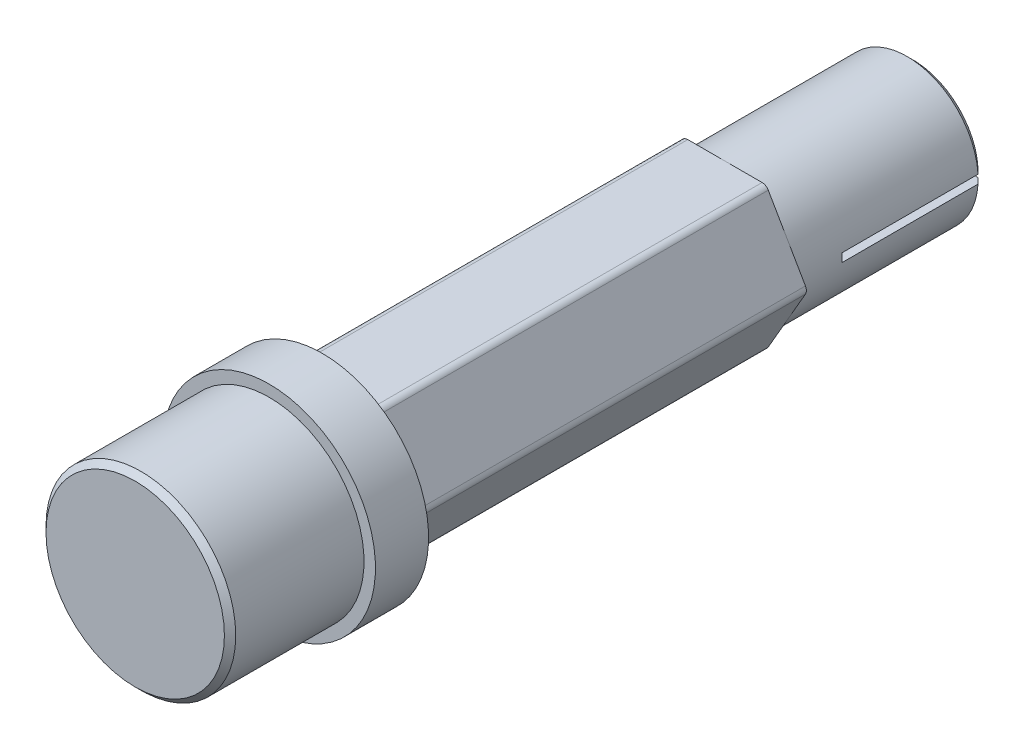
SolidWorks part; units mm, degrees
material "6061-T6 (SS)"
ref_plane "Front Plane" through (0, 0, 0) normal (0, 0, 1) x (1, 0, 0)
ref_plane "Top Plane" through (0, 0, 0) normal (0, 1, 0) x (1, 0, 0)
ref_plane "Right Plane" through (0, 0, 0) normal (1, 0, 0) x (0, 0, -1)
sketch "Sketch1" plane through (0, 0, 0) normal (1, 0, 0) x (0, 0, -1)
  line L0 (0, 0) -> (-33812.0291, 0) construction
  line L1 (0, 0) -> (0, 8.5)
  line L3 (12, 8.5) -> (12, 9.525)
  line L4 (12, 9.525) -> (16.7625, 9.525)
  line L5 (16.7625, 9.525) -> (16.7625, 7.62)
  line L6 (16.7625, 7.62) -> (40.0861, 7.62)
  line L8 (40.0861, 7.62) -> (52.8368, 7.62)
  line L9 (52.8368, 7.62) -> (52.8368, 6.35)
  line L10 (52.8368, 6.35) -> (69.677, 6.35)
  line L11 (69.677, 6.35) -> (69.677, 3.175)
  line L12 (52.5293, 0) -> (0, 0)
  line L16 (0, 8.5) -> (12, 8.5)
  line L17 (69.677, 3.175) -> (54.437, 3.175)
  line L18 (54.437, 3.175) -> (52.5293, 0)
  dimension "D2" = 17
  dimension "D3" = 59
  dimension "D4" = 6.35
  dimension "D5" = 12
  dimension "D6" = 4.7625
  dimension "D7" = 19.05
  dimension "D8" = 15.24
  dimension "D9" = 23.3235
  dimension "D10" = 12.7508
  dimension "D11" = 12.7
  dimension "D12" = 16.8402
  dimension "D13" = 15.24
revolve "Revolve1" add sketch "Sketch1" angle 360 about L0
sketch "Sketch2" plane through (0, 0, -16.7625) normal (0, 0, -1) x (-1, 0, 0)
  line L1 (3.697, 6.4033) -> (-3.697, 6.4033)
  line L2 (-3.697, 6.4033) -> (-7.3939, 0)
  line L3 (-7.3939, 0) -> (-3.697, -6.4033)
  line L4 (-3.697, -6.4033) -> (3.697, -6.4033)
  line L5 (3.697, -6.4033) -> (7.3939, 0)
  line L6 (7.3939, 0) -> (3.697, 6.4033)
  circle A0 centre (0, 0) radius 6.4033 construction
  dimension "D1" = 12.8067
extrude "Cut-Extrude1" cut sketch "Sketch2" along normal up to surface (36.0744 mm away) flip side to cut up to face at (-7.62, 0, -52.8368)
fillet "Fillet1" radius 0.635 6 edges at (3.697, 6.4033, -34.7997) (-3.697, 6.4033, -34.7997) (-7.3939, 0, -34.7997) (-3.697, -6.4033, -34.7997) (3.697, -6.4033, -34.7997) (7.3939, 0, -34.7997)
sketch "Sketch3" plane through (0, 0, -69.677) normal (0, 0, -1) x (-1, 0, 0)
  line L0 (8.9987, 0) -> (0, 0) construction
  line L1 (-8.9987, 0.381) -> (-3.1521, 0.381)
  line L2 (-8.9987, 0.381) -> (-8.9987, -0.381)
  line L3 (-8.9987, -0.381) -> (-3.1521, -0.381)
  line L4 (8.9987, 0.381) -> (8.9987, -0.381)
  line L5 (0, 0) -> (-8.9987, 0) construction
  line L6 (3.1521, -0.381) -> (8.9987, -0.381)
  line L7 (3.1521, 0.381) -> (8.9987, 0.381)
  arc A0 (3.1521, 0.381) -> (-3.1521, 0.381) centre (0, 0) ccw
  arc A2 (-3.1521, -0.381) -> (3.1521, -0.381) centre (0, 0) ccw
  dimension "D1" = 6.35
  dimension "D2" = 0.762
extrude "Cut-Extrude2" cut sketch "Sketch3" against normal blind 12.7
chamfer "Chamfer1" distance 0.508 angle 45 3 edges at (0, 6.35, -69.677) (0, -6.35, -69.677) (-8.5, 0, 0)
ref_plane "Plane1" through (0, 0, -69.1691) normal (0, 0, -1) x (-1, 0, 0)
sketch "Sketch4" plane through (0, 0, -69.1691) normal (0, 0, -1) x (-1, 0, 0)
  circle A0 centre (0, 0) radius 6.35
  arc A1 (-6.3386, -0.381) -> (6.3386, -0.381) centre (0, 0) ccw construction
